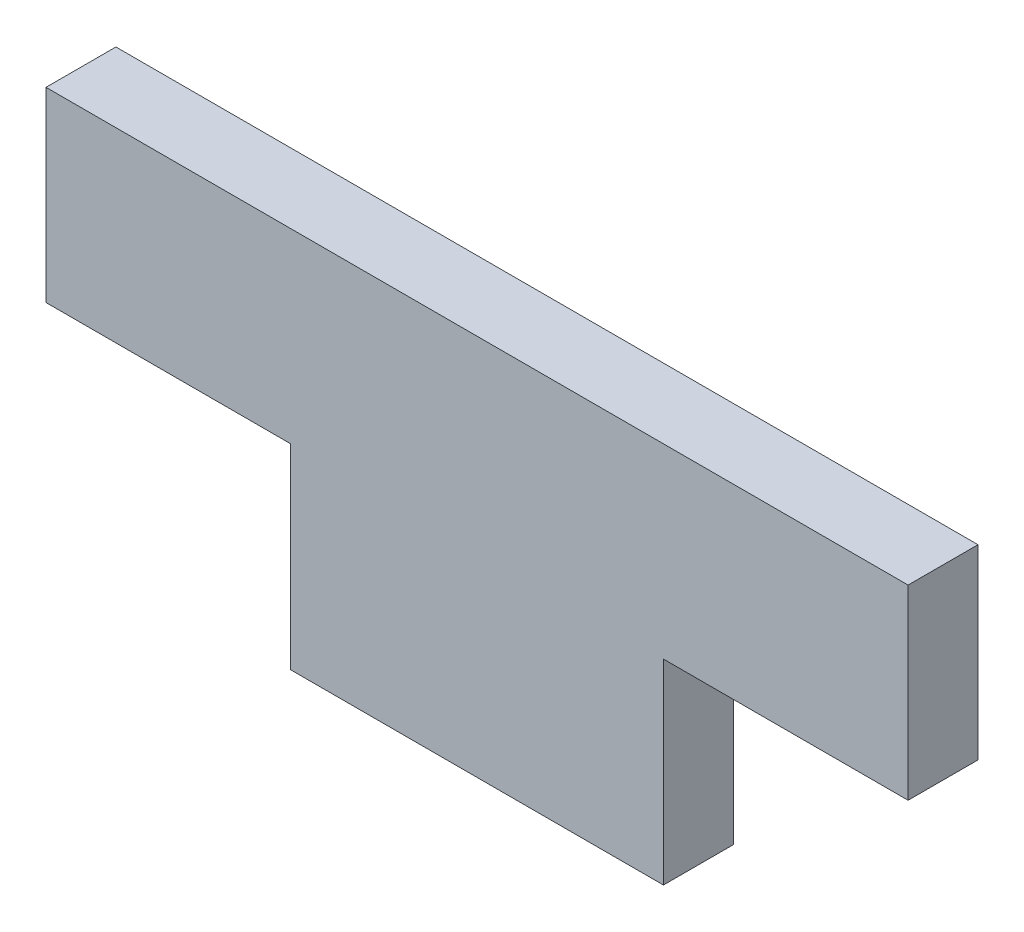
SolidWorks part; units mm, degrees
ref_plane "Front Plane" through (0, 0, 0) normal (0, 0, 1) x (1, 0, 0)
ref_plane "Top Plane" through (0, 0, 0) normal (0, 1, 0) x (1, 0, 0)
ref_plane "Right Plane" through (0, 0, 0) normal (1, 0, 0) x (0, 0, -1)
sketch "Sketch1" plane through (0, 0, 0) normal (0, 0, 1) x (1, 0, 0)
  line L1 (-9.25, -2) -> (9.25, -2)
  line L2 (-9.25, -2) -> (-9.25, 2)
  line L3 (-9.25, 2) -> (9.25, 2)
  line L4 (9.25, -2) -> (9.25, 2)
  line L5 (-9.25, -2) -> (9.25, 2) construction
  line L6 (-9.25, 2) -> (9.25, -2) construction
  point P0 (0, 0)
  dimension "D1" = 18.5
  dimension "D2" = 4
extrude "Boss-Extrude1" add sketch "Sketch1" along normal blind 0.75
sketch "Sketch2" plane through (0, 0, 0) normal (0, 0, 1) x (1, 0, 0)
  line L0 (-9.25, -2) -> (9.25, -2) construction
  line L1 (4, -2) -> (-4, -2)
  line L2 (4, -2) -> (4, -6.2)
  line L3 (4, -6.2) -> (-4, -6.2)
  line L4 (-4, -2) -> (-4, -6.2)
  line L5 (0, 2) -> (0, 0) construction
  line L6 (9.25, 2) -> (-9.25, 2) construction
  dimension "D1" = 8
  dimension "D2" = 4.2
  dimension "D3" = 4
extrude "Boss-Extrude2" add sketch "Sketch2" along normal blind 0.75
mirror "Mirror1" about plane through (0, 0, 0) normal (0, 0, 1) of "Boss-Extrude2", "Boss-Extrude1"
